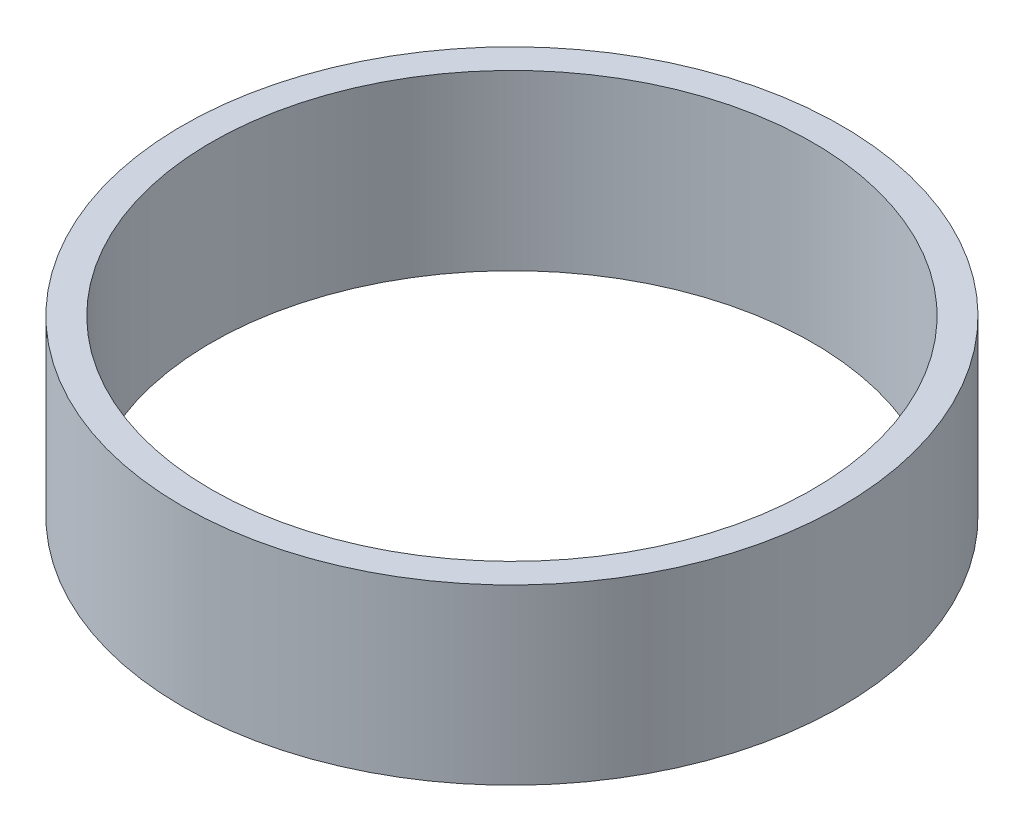
SolidWorks part; units mm, degrees
material "45"
ref_plane "前视基准面" through (0, 0, 0) normal (0, 0, 1) x (1, 0, 0)
ref_plane "上视基准面" through (0, 0, 0) normal (0, 1, 0) x (1, 0, 0)
ref_plane "右视基准面" through (0, 0, 0) normal (1, 0, 0) x (0, 0, -1)
sketch "草图1" plane through (0, 0, 0) normal (0, 1, 0) x (1, 0, 0)
  circle A0 centre (0, 0) radius 52
  circle A1 centre (0, 0) radius 57
  dimension "D1" = 114
  dimension "D2" = 104
extrude "凸台-拉伸1" add sketch "草图1" along normal blind 30
